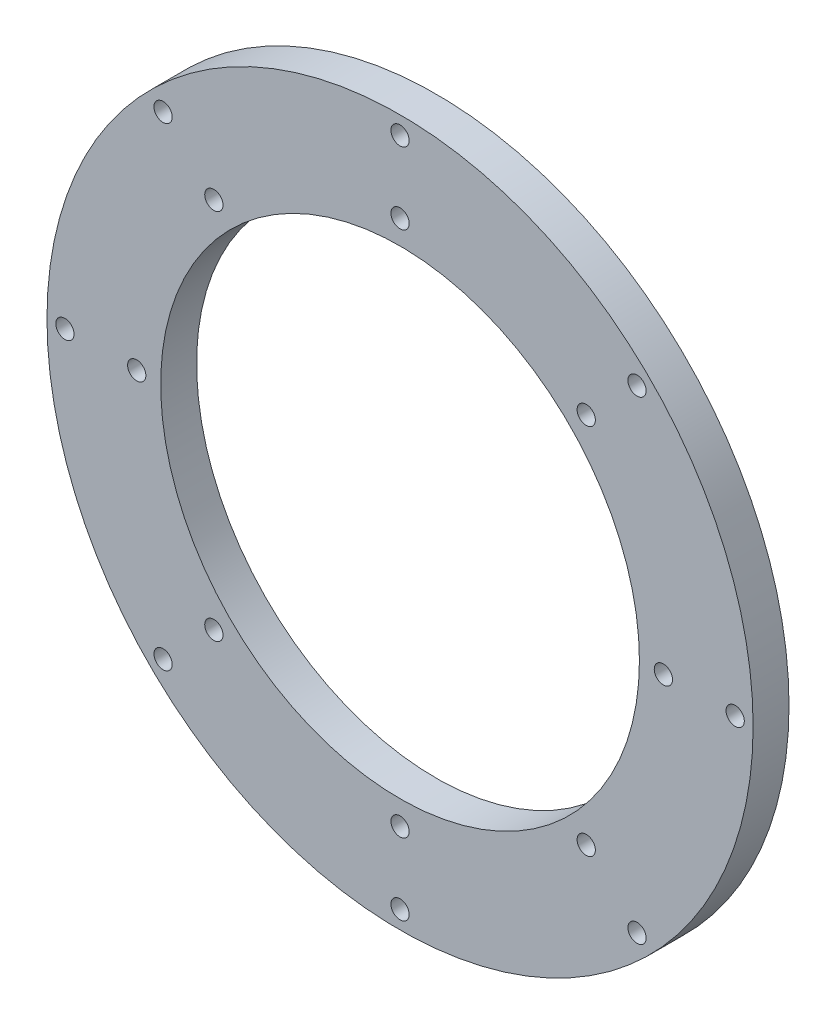
SolidWorks part; units mm, degrees
material "Thornel Mat VMA"
ref_plane "前视基准面" through (0, 0, 0) normal (0, 0, 1) x (1, 0, 0)
ref_plane "上视基准面" through (0, 0, 0) normal (0, 1, 0) x (1, 0, 0)
ref_plane "右视基准面" through (0, 0, 0) normal (1, 0, 0) x (0, 0, -1)
other "Configuration Table"
sketch "草图1" plane through (0, 0, 0) normal (0, 0, 1) x (1, 0, 0)
  circle A0 centre (0, 0) radius 53 construction
  circle A1 centre (0, 0) radius 59
  circle A2 centre (0, 0) radius 50.5
  dimension "D1" = 106
  dimension "D2" = 6
  dimension "D3" = 118
  dimension "D4" = 2.5
extrude "凸台-拉伸1" add sketch "草图1" along normal blind 6
sketch "草图2" plane through (0, 0, 6) normal (0, 0, 1) x (1, 0, 0)
  circle A0 centre (0, 0) radius 56 construction
  circle A1 centre (0, 0) radius 59 construction
  circle A2 centre (0, 56) radius 1.525
  circle A3 centre (39.598, 39.598) radius 1.525
  circle A4 centre (56, 0) radius 1.525
  circle A5 centre (39.598, -39.598) radius 1.525
  circle A6 centre (0, -56) radius 1.525
  circle A7 centre (-39.598, -39.598) radius 1.525
  circle A8 centre (-56, 0) radius 1.525
  circle A9 centre (-39.598, 39.598) radius 1.525
  point P24 (0, 0)
  dimension "D1" = 3
  dimension "D2" = 3.05
  dimension "D3" = 8
extrude "切除-拉伸1" cut sketch "草图2" against normal blind 6
sketch "草图3" plane through (0, 0, 6) normal (0, 0, 1) x (1, 0, 0)
  line L0 (0, 56) -> (0, 0) construction
  line L1 (0, 0) -> (39.598, 39.598) construction
  line L2 (0, 0) -> (21.4303, 51.7373) construction
  circle A0 centre (0, 0) radius 56 construction
  circle A1 centre (21.4303, 51.7373) radius 1.525
  circle A2 centre (51.7373, 21.4303) radius 1.525
  circle A3 centre (51.7373, -21.4303) radius 1.525
  circle A4 centre (21.4303, -51.7373) radius 1.525
  circle A5 centre (-21.4303, -51.7373) radius 1.525
  circle A6 centre (-51.7373, -21.4303) radius 1.525
  circle A7 centre (-51.7373, 21.4303) radius 1.525
  circle A8 centre (-21.4303, 51.7373) radius 1.525
  point P25 (0, 0)
  dimension "D3" = 3.05
  dimension "D1" = 45
  dimension "D2" = 22.5
  dimension "D4" = 8
extrude "切除-拉伸2" [suppressed] cut sketch "草图3" against normal blind 26
hole_wizard "M3 十字槽沉头木螺钉的锥形沉头孔1" [suppressed] positions "草图4" profile "草图5" countersink size "M3" standard "GB"
sketch "草图4" [suppressed] plane through (0, 0, 6) normal (0, 0, 1) x (1, 0, 0)
  point P0 (-21.4303, 51.7373)
sketch "草图5" plane through (-21.4303, 51.7373, 6) normal (1, 0, 0) x (0, -1, 0)
  line L0 (0, 0) -> (0, 6)
  line L1 (0, 6) -> (1.525, 6)
  line L2 (1.525, 6) -> (1.525, 1.775)
  line L3 (1.525, 1.775) -> (3.3, 0)
  line L5 (3.3, 0) -> (0, 0)
  line L6 (-1.525, 1.775) -> (-3.3, 0) construction
  line L11 (0, -6.35) -> (0, 107.95) construction
  dimension "通孔孔直径" = 3.05
  dimension "通孔孔深度" = 6
  dimension "近端锥形沉头孔直径" = 6.6
  dimension "近端锥形沉头孔角度" = 90
pattern_circular "阵列(圆周)1" [suppressed] count 8 over 360
sketch "草图6" plane through (0, 0, 6) normal (0, 0, 1) x (1, 0, 0)
  circle A0 centre (0, 0) radius 50.5
  circle A1 centre (0, 0) radius 40
  dimension "D1" = 101
  dimension "D2" = 80
extrude "凸台-拉伸2" add sketch "草图6" against normal up to surface (6 mm away) up to face at (1.525, 56, 0)
sketch "草图7" plane through (0, 0, 0) normal (0, 0, -1) x (-1, 0, 0)
  circle A0 centre (0, 0) radius 44 construction
  circle A1 centre (0, 0) radius 40 construction
  circle A2 centre (0, 44) radius 1.525
  circle A3 centre (31.1127, 31.1127) radius 1.525
  circle A4 centre (44, 0) radius 1.525
  circle A5 centre (31.1127, -31.1127) radius 1.525
  circle A6 centre (0, -44) radius 1.525
  circle A7 centre (-31.1127, -31.1127) radius 1.525
  circle A8 centre (-44, 0) radius 1.525
  circle A9 centre (-31.1127, 31.1127) radius 1.525
  point P23 (0, 0)
  dimension "D1" = 4
  dimension "D2" = 3.05
  dimension "D3" = 8
extrude "切除-拉伸3" cut sketch "草图7" against normal up to surface (6 mm away) up to face at (1.525, 56, 6)
hole_wizard "M3 十字槽沉头木螺钉的锥形沉头孔2" positions "草图8" profile "草图9" countersink size "M3" standard "GB" end condition through all
sketch "草图8" plane through (0, 0, 0) normal (0, 0, -1) x (-1, 0, 0)
  point P0 (0, 44)
sketch "草图9" plane through (0, 44, 0) normal (1, 0, 0) x (0, 1, 0)
  line L0 (0, 0) -> (0, 6)
  line L1 (0, 6) -> (1.525, 6)
  line L2 (1.525, 6) -> (1.525, 1.775)
  line L3 (1.525, 1.775) -> (3.3, 0)
  line L5 (3.3, 0) -> (0, 0)
  line L6 (-1.525, 1.775) -> (-3.3, 0) construction
  line L11 (0, -6.35) -> (0, 107.95) construction
  dimension "通孔孔直径" = 3.05
  dimension "通孔孔深度" = 6
  dimension "近端锥形沉头孔直径" = 6.6
  dimension "近端锥形沉头孔角度" = 90
pattern_circular "阵列(圆周)2" count 8 over 360 about axis through (0, 0, 0) along (0, 0, 1) of "M3 十字槽沉头木螺钉的锥形沉头孔2"
equation "\"D2@草图3\"=\"D1@草图3\"/2"
